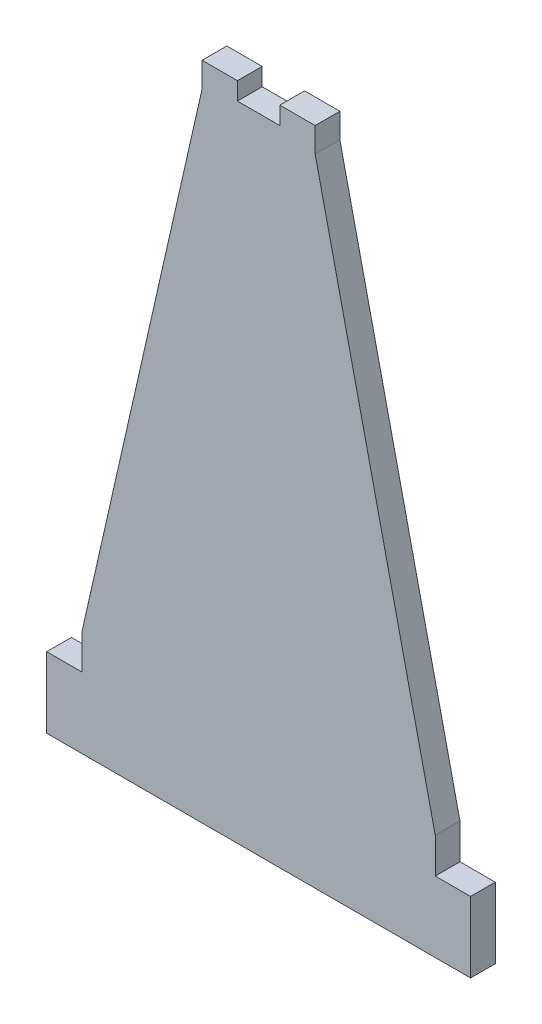
SolidWorks part; units mm, degrees
material "PBT General Purpose"
ref_plane "Front Plane" through (0, 0, 0) normal (0, 0, 1) x (1, 0, 0)
ref_plane "Top Plane" through (0, 0, 0) normal (0, 1, 0) x (1, 0, 0)
ref_plane "Right Plane" through (0, 0, 0) normal (1, 0, 0) x (0, 0, -1)
sketch "frame_outline" plane through (0, 0, 0) normal (0, 0, 1) x (1, 0, 0)
  line L110 (0, 0) -> (6, 0)
  line L117 (6, 0) -> (6, 1)
  line L118 (6, 1) -> (5.5, 1)
  line L119 (5.5, 1) -> (5.5, 1.5)
  line L120 (5.5, 1.5) -> (3.8, 9)
  line L121 (3.8, 9) -> (3.8, 9.35)
  line L122 (3.8, 9.35) -> (3.3, 9.35)
  line L123 (3.3, 9.35) -> (3.3, 9.1)
  line L124 (3.3, 9.1) -> (2.7, 9.1)
  line L125 (2.7, 9.1) -> (2.7, 9.35)
  line L126 (2.7, 9.35) -> (2.2, 9.35)
  line L127 (2.2, 9.35) -> (2.2, 9)
  line L128 (2.2, 9) -> (0.5, 1.5)
  line L129 (0.5, 1.5) -> (0.5, 1)
  line L130 (0.5, 1) -> (0, 1)
  line L131 (0, 1) -> (0, 0)
  line L132 (3, 9.1) -> (3, 0) construction
  dimension "D1" = 5
  dimension "D2" = 0.5
  dimension "D3" = 1
  dimension "D4" = 0.5
  dimension "D5" = 8
  dimension "D6" = 0.6
  dimension "D7" = 0.25
  dimension "D8" = 0.5
  dimension "D9" = 0.1
extrude "Boss-Extrude1" add sketch "frame_outline" along normal mid plane 0.35
equation "\"t\"= 0.25'thickness of the sheets"
equation "\"t_cf\" = 0.115'thickness of single carbon fiber layer"
equation "\"t_kapton\" = 0.025'thickness of single Kapton flex layer"
equation "\"t_fr4\" = 0.1'thickness of FR4 with copper layer"
equation "\"joint_flex\"= 0.1'Width of flextures gap"
equation "\"joint_flex_eff\"= 0.02'Width of flecture after castelation"
equation "\"joint_fold\"= 0.2'Width of folding joints for 90deg fold"
equation "\"gap_tolerance\"= 0.002'Width to have interfecence fit between carbon fiber inserts"
equation "\"assemble_angle\"= 90'Angle of assembly parts"
equation "\"D1@Boss-Extrude1\"=0.35"
equation "\"link_lift\"= 0.5'Actuation linkage amplification for the lift motion"
equation "\"link_swing\"= 0.45'Actuation linkage amplification for the swing motion"
